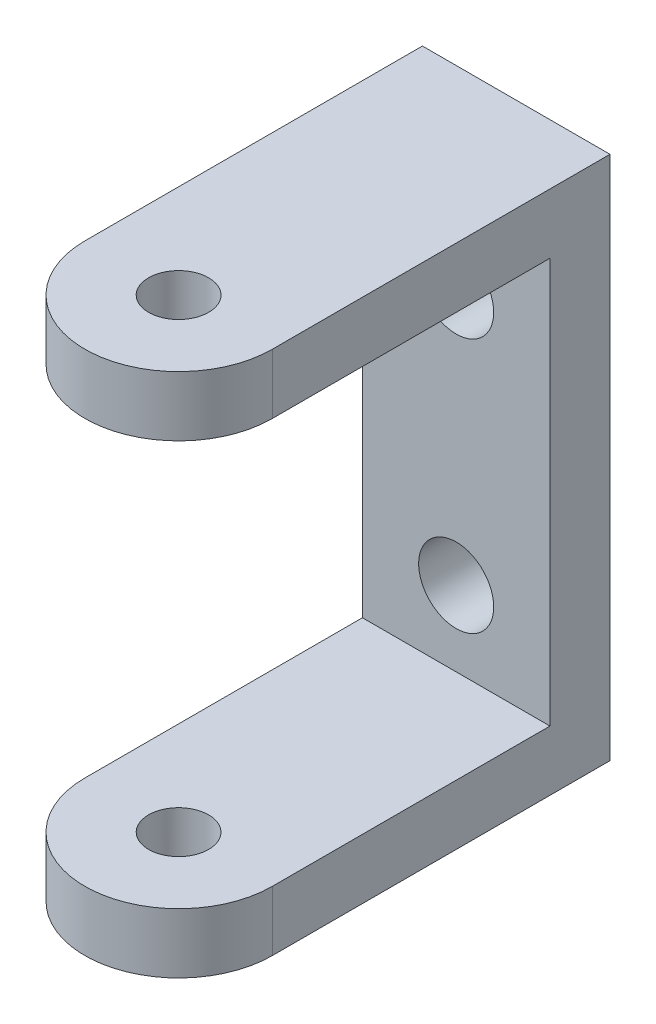
SolidWorks part; units mm, degrees
ref_plane "Piano frontale" through (0, 0, 0) normal (0, 0, 1) x (1, 0, 0)
ref_plane "Piano superiore" through (0, 0, 0) normal (0, 1, 0) x (1, 0, 0)
ref_plane "Piano destro" through (0, 0, 0) normal (1, 0, 0) x (0, 0, -1)
sketch "Schizzo1" plane through (0, 0, 0) normal (0, 0, 1) x (1, 0, 0)
  line L1 (12.5, -35) -> (-12.5, -35)
  line L2 (12.5, -35) -> (12.5, 35)
  line L3 (12.5, 35) -> (-12.5, 35)
  line L4 (-12.5, -35) -> (-12.5, 35)
  line L5 (12.5, -35) -> (-12.5, 35) construction
  line L6 (12.5, 35) -> (-12.5, -35) construction
  point P0 (0, 0)
  dimension "D1" = 70
  dimension "D2" = 25
extrude "Estrusione-Estrusione1" add sketch "Schizzo1" along normal blind 8
sketch "Schizzo2" plane through (0, 0, 8) normal (0, 0, 1) x (1, 0, 0)
  line L0 (12.5, -35) -> (12.5, 35) construction
  line L1 (-12.5, 35) -> (12.5, 35)
  line L2 (-12.5, 35) -> (-12.5, 27)
  line L3 (-12.5, 27) -> (12.5, 27)
  line L4 (12.5, 35) -> (12.5, 27)
  line L6 (-12.5, -35) -> (12.5, -35)
  line L7 (-12.5, -35) -> (-12.5, -27)
  line L8 (-12.5, -27) -> (12.5, -27)
  line L9 (12.5, -35) -> (12.5, -27)
  dimension "D1" = 8
  dimension "D2" = 8
extrude "Estrusione-Estrusione2" add sketch "Schizzo2" along normal blind 49.5
sketch "Schizzo3" plane through (0, 35, 0) normal (0, 1, 0) x (1, 0, 0)
  line L0 (-12.5, -57.5) -> (-12.5, 0) construction
  line L1 (12.5, -57.5) -> (-12.5, -57.5) construction
  line L2 (-12.5, -45) -> (-12.5, -57.5)
  line L3 (-12.5, -57.5) -> (12.5, -57.5)
  line L4 (12.5, -57.5) -> (12.5, -45)
  arc A0 (-12.5, -45) -> (12.5, -45) centre (0, -45) ccw
  circle A1 centre (0, -45) radius 4
  line M3 (-12.5, 0) -> (-12.5, -57.5)
  line M4 (-12.5, -57.5) -> (12.5, -57.5)
  line M5 (12.5, -57.5) -> (12.5, 0)
  dimension "D1" = 25
  dimension "D2" = 8
extrude "Taglio-Estrusione1" cut sketch "Schizzo3" against normal blind 70 contours A0 M3 M4 | A0 L3 M5 | A1
sketch "Schizzo4" plane through (0, 0, 8) normal (0, 0, 1) x (1, 0, 0)
  circle A0 centre (0, 17) radius 5
  circle A1 centre (0, -17) radius 5
  point P4 (-3.8598, -17.0312)
  point P6 (0, 0)
  point P7 (0, 0)
  point P8 (0, 17)
  dimension "D3" = 10
  dimension "D4" = 10
  dimension "D1" = 34
  dimension "D2" = 17
extrude "Taglio-Estrusione2" cut sketch "Schizzo4" against normal blind 8
